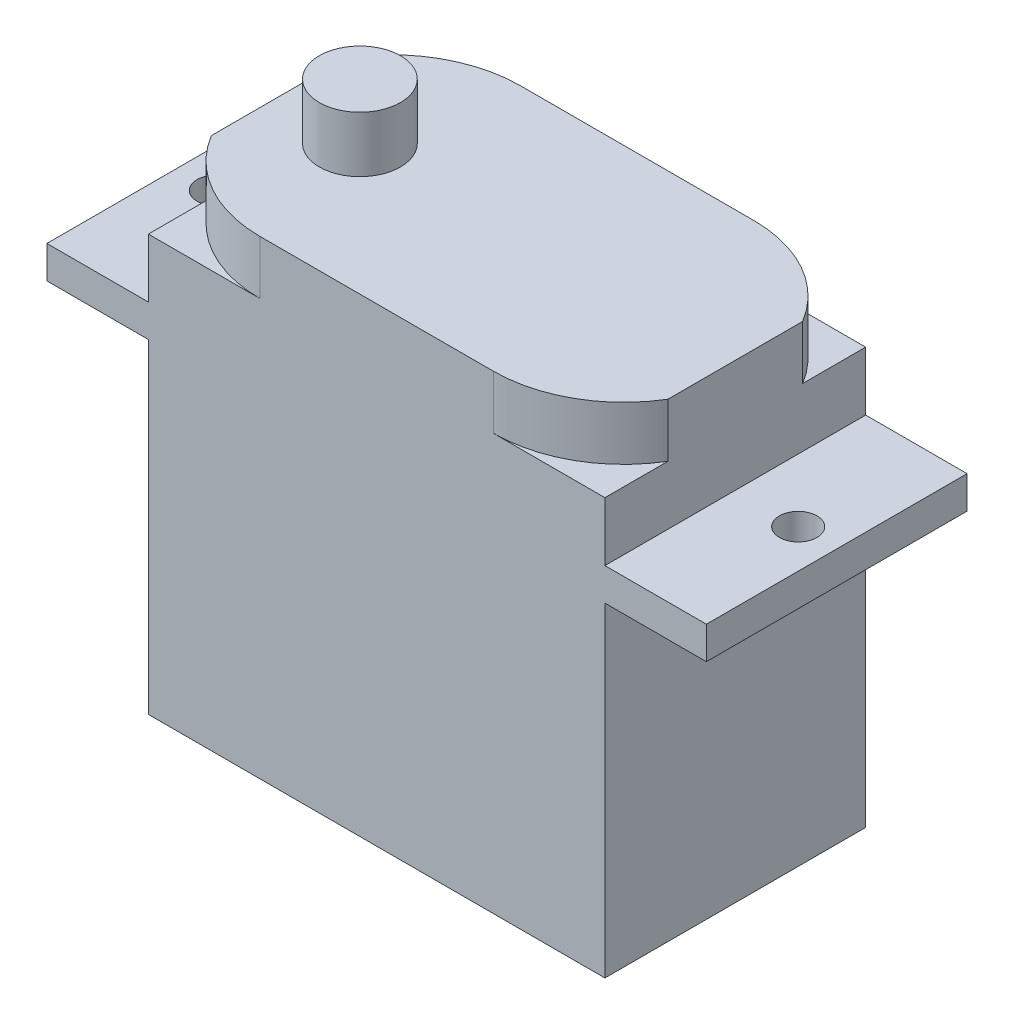
SolidWorks part; units mm, degrees
ref_plane "Plan de face" through (0, 0, 0) normal (0, 0, 1) x (1, 0, 0)
ref_plane "Plan de dessus" through (0, 0, 0) normal (0, 1, 0) x (1, 0, 0)
ref_plane "Plan de droite" through (0, 0, 0) normal (1, 0, 0) x (0, 0, -1)
sketch "Esquisse1" plane through (0, 0, 0) normal (0, 0, 1) x (1, 0, 0)
  line L1 (-11.25, -10.25) -> (11.25, -10.25)
  line L2 (-11.25, -10.25) -> (-11.25, 10.25)
  line L3 (-11.25, 10.25) -> (11.25, 10.25)
  line L4 (11.25, -10.25) -> (11.25, 10.25)
  line L5 (-11.25, -10.25) -> (11.25, 10.25) construction
  line L6 (-11.25, 10.25) -> (11.25, -10.25) construction
  point P0 (0, 0)
  dimension "D1" = 20.5
  dimension "D2" = 22.5
extrude "Extrusion1" add sketch "Esquisse1" along normal blind 12.85
sketch "Esquisse2" plane through (0, 10.25, 0) normal (0, 1, 0) x (1, 0, 0)
  line L3 (-11.25, -12.85) -> (-11.25, 0) construction
  line L5 (-5.75, 0) -> (5.75, 0)
  line L6 (-5.75, -12.85) -> (5.75, -12.85)
  line L8 (-11.25, -9.7462) -> (-11.25, -3.1038)
  line L10 (11.25, -12.85) -> (11.25, 0) construction
  line L11 (11.25, -3.1038) -> (11.25, -9.7462)
  line L13 (0, -12.85) -> (0, -15.3763) construction
  arc A0 (-11.25, -9.7462) -> (-5.75, -12.85) centre (-5.75, -6.425) ccw
  arc A1 (11.25, -9.7462) -> (5.75, -12.85) centre (5.75, -6.425) cw
  arc A2 (-5.75, 0) -> (-11.25, -3.1038) centre (-5.75, -6.425) ccw
  arc A3 (5.75, 0) -> (11.25, -3.1038) centre (5.75, -6.425) cw
  dimension "D1" = 5.5
extrude "Extrusion2" add sketch "Esquisse2" along normal blind 2.65
sketch "Esquisse3" plane through (-11.25, 0, 0) normal (-1, 0, 0) x (0, 0, 1)
  line L0 (0, 10.25) -> (0, -10.25) construction
  line L1 (0, 7.35) -> (12.85, 7.35)
  line L2 (0, 7.35) -> (0, 5.75)
  line L3 (0, 5.75) -> (12.85, 5.75)
  line L4 (12.85, 7.35) -> (12.85, 5.75)
  line L5 (12.85, 10.25) -> (12.85, -10.25) construction
  line L6 (12.85, -10.25) -> (0, -10.25) construction
  dimension "D1" = 16
  dimension "D2" = 1.6
extrude "Extrusion3" add sketch "Esquisse3" along normal blind 5
sketch "Esquisse5" plane through (0, 7.35, 0) normal (0, 1, 0) x (1, 0, 0)
  line L0 (-16.25, -12.85) -> (-11.25, -12.85) construction
  line L1 (-16.25, -12.85) -> (-16.25, 0) construction
  circle A0 centre (-14.35, -6.425) radius 0.925
  dimension "D1" = 1.85
  dimension "D2" = 6.425
  dimension "D3" = 1.9
extrude "Extrusion5" cut sketch "Esquisse5" against normal blind 2.75
mirror "Symétrie1" about plane through (0, 0, 0) normal (1, 0, 0) of "Extrusion5", "Extrusion3"
sketch "Esquisse4" plane through (0, 12.9, 0) normal (0, 1, 0) x (1, 0, 0)
  line L0 (5.75, 0) -> (-5.75, 0) construction
  line L1 (-11.25, -12.85) -> (-11.25, 0) construction
  circle A0 centre (-7.25, -6.425) radius 2
  dimension "D2" = 4
  dimension "D1" = 6.425
  dimension "D3" = 4
extrude "Extrusion4" add sketch "Esquisse4" along normal blind 2.75
